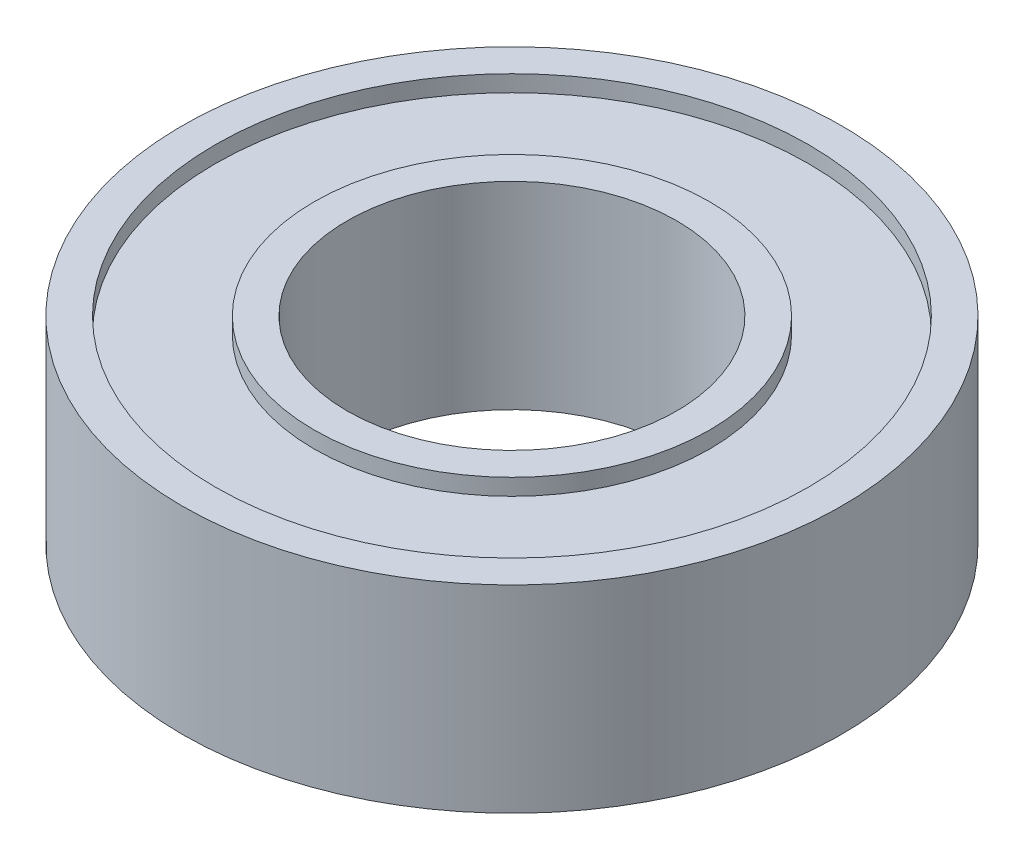
SolidWorks part; units mm, degrees
ref_plane "Front Plane" through (0, 0, 0) normal (0, 0, 1) x (1, 0, 0)
ref_plane "Top Plane" through (0, 0, 0) normal (0, 1, 0) x (1, 0, 0)
ref_plane "Right Plane" through (0, 0, 0) normal (1, 0, 0) x (0, 0, -1)
sketch "Sketch1" plane through (0, 0, 0) normal (0, 1, 0) x (1, 0, 0)
  circle A0 centre (0, 0) radius 5
  circle A1 centre (0, 0) radius 2.5
  dimension "D1" = 10
  dimension "D2" = 5
extrude "Boss-Extrude1" add sketch "Sketch1" along normal blind 3
sketch "Sketch2" plane through (0, 0, 0) normal (0, -1, 0) x (1, 0, 0)
  circle A0 centre (0, 0) radius 3
  circle A1 centre (0, 0) radius 4.5
  dimension "D1" = 6
  dimension "D2" = 9
extrude "Cut-Extrude1" cut sketch "Sketch2" against normal blind 0.25
sketch "Sketch3" plane through (0, 3, 0) normal (0, 1, 0) x (1, 0, 0)
  circle A0 centre (0, 0) radius 3
  circle A1 centre (0, 0) radius 4.5
  dimension "D1" = 6
  dimension "D2" = 9
extrude "Cut-Extrude2" cut sketch "Sketch3" against normal blind 0.25
